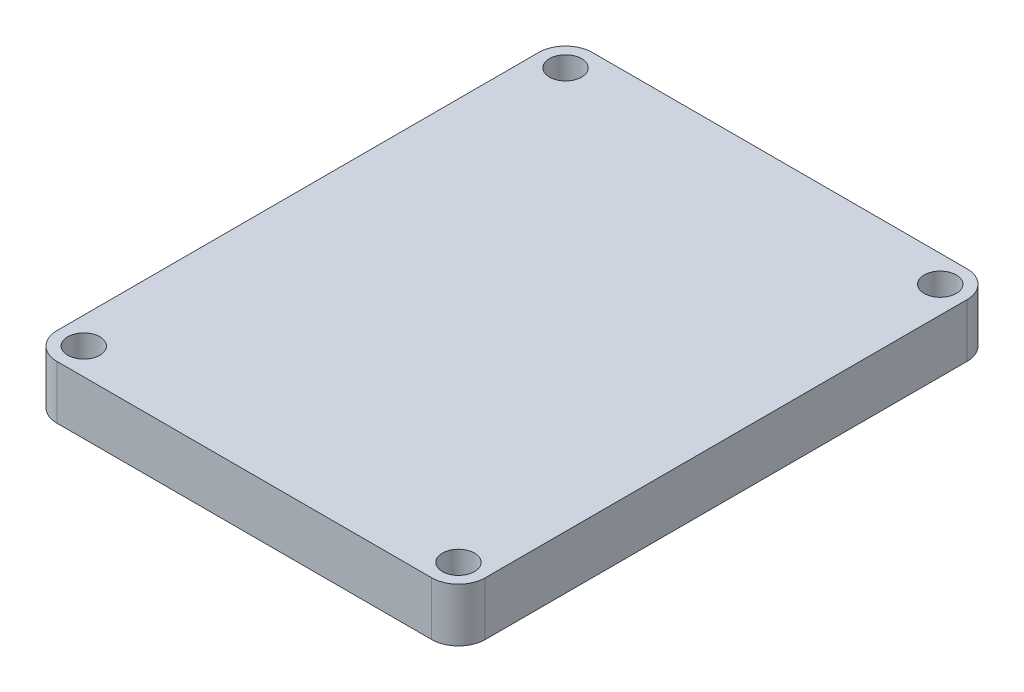
SolidWorks part; units mm, degrees
material "ABS PC"
ref_plane "Front Plane" through (0, 0, 0) normal (0, 0, 1) x (1, 0, 0)
ref_plane "Top Plane" through (0, 0, 0) normal (0, 1, 0) x (1, 0, 0)
ref_plane "Right Plane" through (0, 0, 0) normal (1, 0, 0) x (0, 0, -1)
sketch "Sketch1" plane through (0, 0, 0) normal (0, 1, 0) x (1, 0, 0)
  line L0 (-70.6896, 40.7853) -> (-70.6896, -59.2147)
  line L1 (-70.6896, 40.7853) -> (9.3104, 40.7853)
  line L2 (-70.6896, -59.2147) -> (9.3104, -59.2147)
  line L3 (9.3104, 40.7853) -> (9.3104, -59.2147)
  line L4 (-70.6896, -59.2147) -> (-70.6896, -54.2147)
  line L5 (-70.6896, -59.2147) -> (-65.6896, -59.2147)
  line L6 (-70.6896, -54.2147) -> (-65.6896, -54.2147)
  line L7 (-65.6896, -59.2147) -> (-65.6896, -54.2147)
  line L8 (-70.6896, -9.2147) -> (9.3104, -9.2147) construction
  line L9 (-30.6896, 40.7853) -> (-30.6896, -59.2147) construction
  circle A0 centre (-65.6896, -54.2147) radius 3
  circle A1 centre (-65.6896, 35.7853) radius 3
  circle A2 centre (4.3104, -54.2147) radius 3
  circle A3 centre (4.3104, 35.7853) radius 3
  dimension "D5" = 6
  dimension "D1" = 80
  dimension "D2" = 100
  dimension "D3" = 5
  dimension "D4" = 5
extrude "Boss-Extrude2" add sketch "Sketch1" along normal blind 10 contours A0 L7 L2 L3 L1 L0 L6 A3 A1 A2 | A0 L6 L0 L2 L7
fillet "Fillet1" radius 5 1 edges at (-70.6896, 5, 59.2147)
fillet "Fillet2" radius 5 3 edges at (9.3104, 5, 59.2147) (9.3104, 5, -40.7853) (-70.6896, 5, -40.7853)
